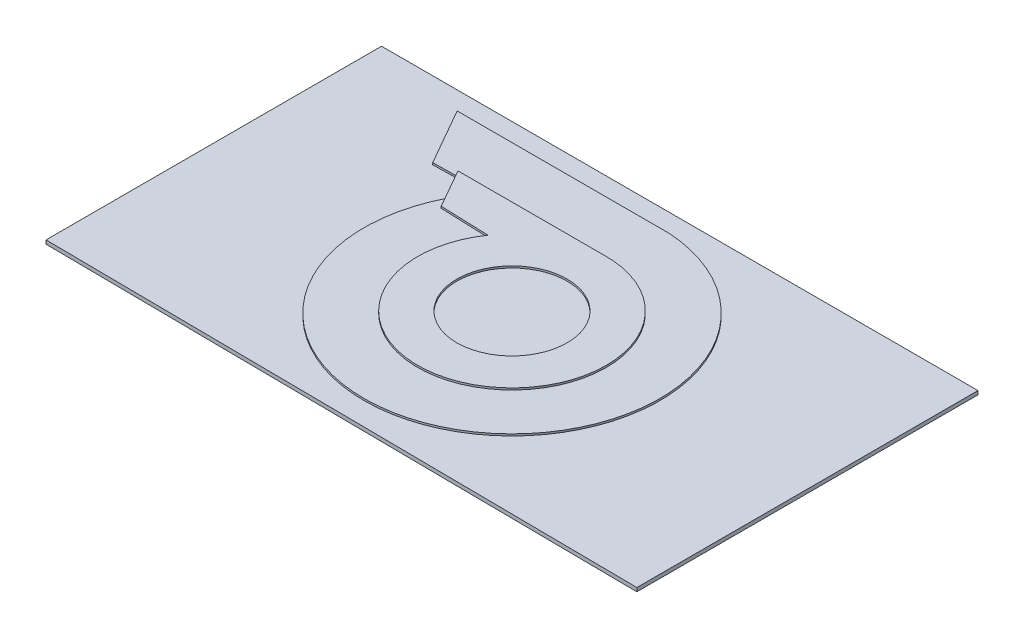
SolidWorks part; units mm, degrees
ref_plane "Front Plane" through (0, 0, 0) normal (0, 0, 1) x (1, 0, 0)
ref_plane "Top Plane" through (0, 0, 0) normal (0, 1, 0) x (1, 0, 0)
ref_plane "Right Plane" through (0, 0, 0) normal (1, 0, 0) x (0, 0, -1)
sketch "Sketch2" plane through (0, 0, 0) normal (0, 1, 0) x (1, 0, 0)
  line L0 (-70, 35) -> (70, 35) construction
  line L1 (70, 35) -> (70, -35) construction
  line L2 (70, -35) -> (-70, -35) construction
  line L3 (-70, -35) -> (-70, 35) construction
  line L4 (-80, 45) -> (80, 45) construction
  line L5 (80, 45) -> (80, -45) construction
  line L8 (80, -45) -> (-80, -45) construction
  line L9 (-80, -45) -> (-80, 45) construction
  line L10 (-80, 45) -> (80, -45) construction
  line L11 (-80, -45) -> (80, 45) construction
sketch "Sketch3" plane through (0, 0, 0) normal (0, 1, 0) x (1, 0, 0)
  line L0 (-80, 45) -> (80, 45)
  line L1 (80, 45) -> (80, -46.5056)
  line L2 (80, -46.5056) -> (-80, -45)
  line L3 (-80, -45) -> (-80, 45)
extrude "Boss-Extrude1" add sketch "Sketch3" along normal blind 1
sketch "Sketch4" plane through (0, 0, 0) normal (0, -1, 0) x (1, 0, 0)
  line L1 (70, 35) -> (-70, 35) construction
  line L4 (-70.35, 37.9795) -> (-70.35, 32.0205) construction
  line L5 (-70.35, 35) -> (-73, 35) construction
  line L6 (-69.65, 37.9795) -> (-69.65, 32.0205) construction
  line L7 (-70, 35) -> (-70, -35) construction
  line L8 (-70, 35) -> (-70, -35) construction
  line L9 (-70.35, 35) -> (-73.35, 35) construction
  line L10 (-69.65, 35) -> (-66.65, 35) construction
  circle A2 centre (-70, 35) radius 3 construction
  point P11 (70, 35)
  point P12 (70, -35)
  point P13 (-70, -35)
  point P15 (-70.35, 35)
  point P16 (-70.35, 35)
  point P17 (-70, 27.2435)
  point P20 (-69.65, 35)
  point P22 (-67, 35)
  line B0 (-70.35, 35) -> (-69.65, 35) construction
  line B1 (-70.35, 37.9795) -> (-70.35, 32.0205)
  line B2 (-69.65, 37.9795) -> (-69.65, 32.0205)
  ellipse B3 centre (-69.65, 35) end of major axis (-66.65, 35) minor radius 2.9795 (-69.65, 37.9795) -> (-69.65, 32.0205) cw
  ellipse B4 centre (-70.35, 35) end of major axis (-73.35, 35) minor radius 2.9795 (-70.35, 37.9795) -> (-70.35, 32.0205) ccw
  line B5 (69.65, 35) -> (70.35, 35) construction
  line B6 (69.65, 37.9795) -> (69.65, 32.0205)
  line B7 (70.35, 37.9795) -> (70.35, 32.0205)
  ellipse B8 centre (70.35, 35) end of major axis (73.35, 35) minor radius 2.9795 (70.35, 37.9795) -> (70.35, 32.0205) cw
  ellipse B9 centre (69.65, 35) end of major axis (66.65, 35) minor radius 2.9795 (69.65, 37.9795) -> (69.65, 32.0205) ccw
  line B10 (69.65, -35) -> (70.35, -35) construction
  line B11 (69.65, -32.0205) -> (69.65, -37.9795)
  line B12 (70.35, -32.0205) -> (70.35, -37.9795)
  ellipse B13 centre (70.35, -35) end of major axis (73.35, -35) minor radius 2.9795 (70.35, -32.0205) -> (70.35, -37.9795) cw
  ellipse B14 centre (69.65, -35) end of major axis (66.65, -35) minor radius 2.9795 (69.65, -32.0205) -> (69.65, -37.9795) ccw
  line B15 (-70.35, -32.0205) -> (-70.35, -37.9795)
  line B16 (-69.65, -32.0205) -> (-69.65, -37.9795)
  ellipse B17 centre (-69.65, -35) end of major axis (-66.65, -35) minor radius 2.9795 (-69.65, -32.0205) -> (-69.65, -37.9795) cw
  ellipse B18 centre (-70.35, -35) end of major axis (-73.35, -35) minor radius 2.9795 (-70.35, -32.0205) -> (-70.35, -37.9795) ccw
  dimension "D2" = 3
  dimension "D3" = 3
sketch_block_instance "Block2-1"
sketch_block "Block2" parameters "D1"=0.7
sketch_block_instance "Block2-2"
sketch_block_instance "Block2-3"
sketch_block_instance "Block2-4"
extrude "Boss-Extrude2" add sketch "Sketch4" along normal blind 2.7
sketch "Sketch5" plane through (0, 0, 0) normal (0, -1, 0) x (1, 0, 0)
  circle A0 centre (-70, 35) radius 3
  circle A1 centre (70, 35) radius 3
  circle A2 centre (70, -35) radius 3
  circle A3 centre (-70, -35) radius 3
extrude "Cut-Extrude1" cut sketch "Sketch5" along normal blind 2 flip side to cut
sketch "Sketch6" plane through (0, 1, 0) normal (0, 1, 0) x (1, 0, 0)
  line L0 (-75.54, 32.8948) -> (74.46, 32.8948) construction
  line L14 (-54.317, 39.6022) -> (2.6047, 39.6022)
  line L15 (-54.317, 39.6022) -> (-45.5799, 24.3208)
  line L16 (-45.5799, 24.3208) -> (-31.1854, 24.5478)
  line L17 (-39.7662, 24.5093) -> (-33.5956, 14.1723)
  line L18 (-33.5956, 14.1723) -> (-20.8154, 14.3738)
  line L19 (-39.7662, 24.5093) -> (-0.608, 25.2887)
  circle A7 centre (0, 0) radius 14.8075
  arc A8 (-31.1854, 24.5478) -> (2.6047, 39.6022) centre (0, 0) ccw
  arc A9 (-20.8154, 14.3738) -> (-0.608, 25.2887) centre (0, 0) ccw
  point P2 (0, 0)
  point P3 (0, 0)
sketch "Sketch7" plane through (0, 1, 0) normal (0, 1, 0) x (1, 0, 0)
  line L0 (-54.317, 39.6022) -> (2.6047, 39.6022)
  line L1 (-54.317, 39.6022) -> (-45.5799, 24.3208)
  line L2 (-45.5799, 24.3208) -> (-31.1854, 24.5478)
  arc A0 (-31.1854, 24.5478) -> (2.6047, 39.6022) centre (0, 0) ccw
  point P5 (0, 0)
extrude "Boss-Extrude3" add sketch "Sketch7" along normal blind 0.5
sketch "Sketch8" plane through (0, 1, 0) normal (0, 1, 0) x (1, 0, 0)
  line L0 (-39.774, 25.2887) -> (-33.8103, 14.8309)
  line L1 (-33.8103, 14.8309) -> (-20.8154, 14.3738)
  line L2 (-39.774, 25.2887) -> (-0.608, 25.2887)
  arc A0 (-20.8154, 14.3738) -> (-0.608, 25.2887) centre (0, 0) ccw
  point P5 (0, 0)
extrude "Boss-Extrude4" add sketch "Sketch8" along normal blind 1
sketch "Sketch9" plane through (0, 1, 0) normal (0, 1, 0) x (1, 0, 0)
  circle A0 centre (0, 0) radius 14.8075
  point P2 (0, 0)
extrude "Cut-Extrude2" cut sketch "Sketch9" along normal blind 0.5 from offset 0.5
